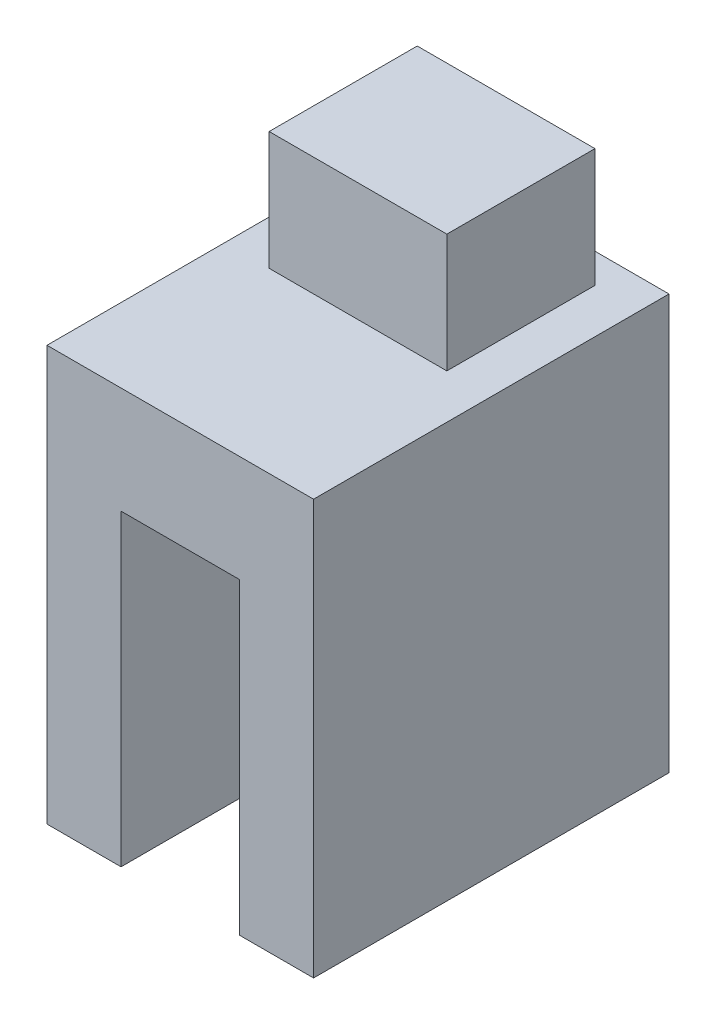
SolidWorks part; units mm, degrees
ref_plane "Front Plane" through (0, 0, 0) normal (0, 0, 1) x (1, 0, 0)
ref_plane "Top Plane" through (0, 0, 0) normal (0, 1, 0) x (1, 0, 0)
ref_plane "Right Plane" through (0, 0, 0) normal (1, 0, 0) x (0, 0, -1)
sketch "Sketch3" plane through (0, 0, 0) normal (0, 1, 0) x (1, 0, 0)
  line L1 (-7.1438, -9.525) -> (7.1437, -9.525)
  line L2 (-7.1438, -9.525) -> (-7.1438, 9.525)
  line L3 (-7.1438, 9.525) -> (7.1437, 9.525)
  line L4 (7.1437, -9.525) -> (7.1437, 9.525)
  line L5 (-7.1438, -9.525) -> (7.1437, 9.525) construction
  line L6 (-7.1438, 9.525) -> (7.1437, -9.525) construction
  point P0 (0, 0)
  dimension "D1" = 14.2875
  dimension "D2" = 19.05
extrude "Boss-Extrude1" add sketch "Sketch3" along normal blind 22.225
sketch "Sketch4" plane through (0, 22.225, 0) normal (0, 1, 0) x (1, 0, 0)
  line L1 (-4.7625, 7.9375) -> (4.7625, 7.9375)
  line L2 (-4.7625, 7.9375) -> (-4.7625, 0)
  line L3 (-4.7625, 0) -> (4.7625, 0)
  line L4 (4.7625, 7.9375) -> (4.7625, 0)
  line L5 (7.1437, 9.525) -> (-7.1438, 9.525) construction
  point P4 (0, 7.9375)
  point P5 (0, 9.525)
  dimension "D1" = 9.525
  dimension "D2" = 7.9375
  dimension "D4" = 1.5875
extrude "Boss-Extrude2" add sketch "Sketch4" along normal blind 6.35 contours L3 L4 L1 L2
sketch "Sketch5" plane through (0, 0, 0) normal (0, -1, 0) x (1, 0, 0)
  line L0 (-7.1438, 9.525) -> (7.1437, 9.525) construction
  line L1 (3.175, -9.525) -> (-3.175, -9.525)
  line L2 (3.175, -9.525) -> (3.175, 9.525)
  line L3 (3.175, 9.525) -> (-3.175, 9.525)
  line L4 (-3.175, -9.525) -> (-3.175, 9.525)
  line L5 (3.175, -9.525) -> (-3.175, 9.525) construction
  line L6 (3.175, 9.525) -> (-3.175, -9.525) construction
  point P0 (0, 0)
  dimension "D1" = 6.35
extrude "Cut-Extrude1" cut sketch "Sketch5" against normal blind 16.51
